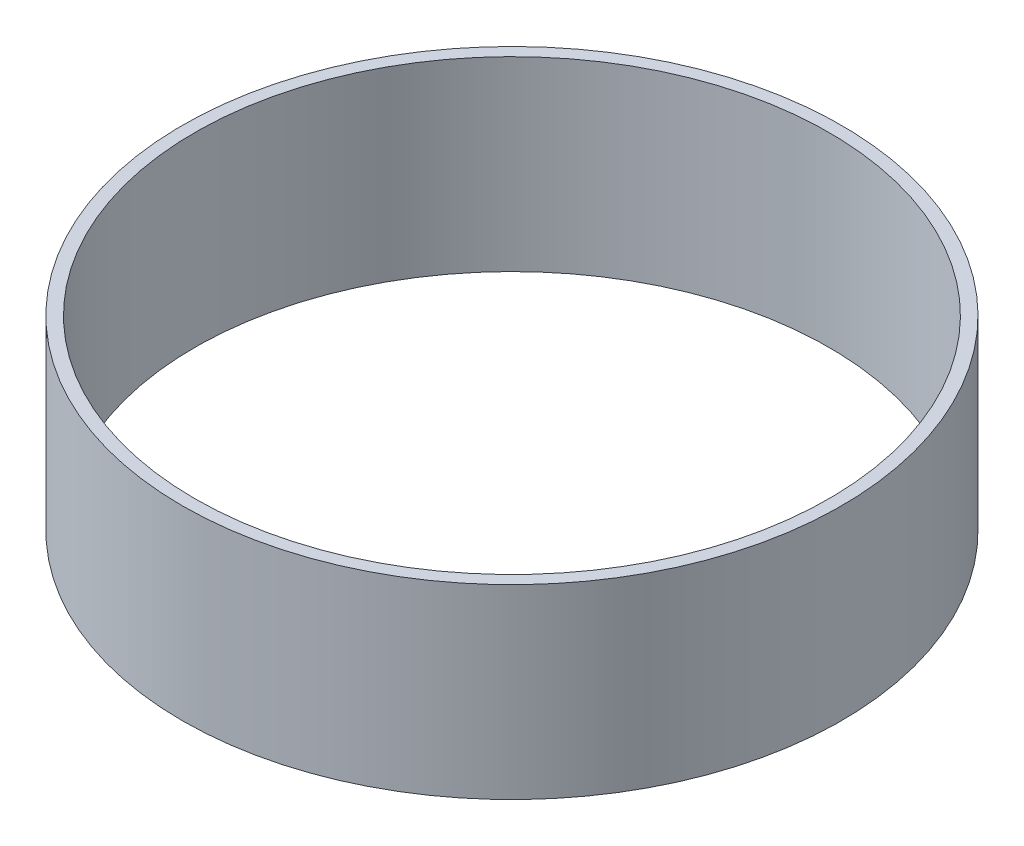
SolidWorks part; units mm, degrees
material "ABS"
ref_plane "Front Plane" through (0, 0, 0) normal (0, 0, 1) x (1, 0, 0)
ref_plane "Top Plane" through (0, 0, 0) normal (0, 1, 0) x (1, 0, 0)
ref_plane "Right Plane" through (0, 0, 0) normal (1, 0, 0) x (0, 0, -1)
sketch "Sketch1" plane through (0, 0, 0) normal (0, 1, 0) x (1, 0, 0.0044)
  circle A0 centre (-29.3916, 2.6114) radius 26.506
  circle A1 centre (-29.3916, 2.6114) radius 25.506
  dimension "D2" = 51.012
  dimension "D1" = 1
extrude "Boss-Extrude1" add sketch "Sketch1" along normal blind 14.97
